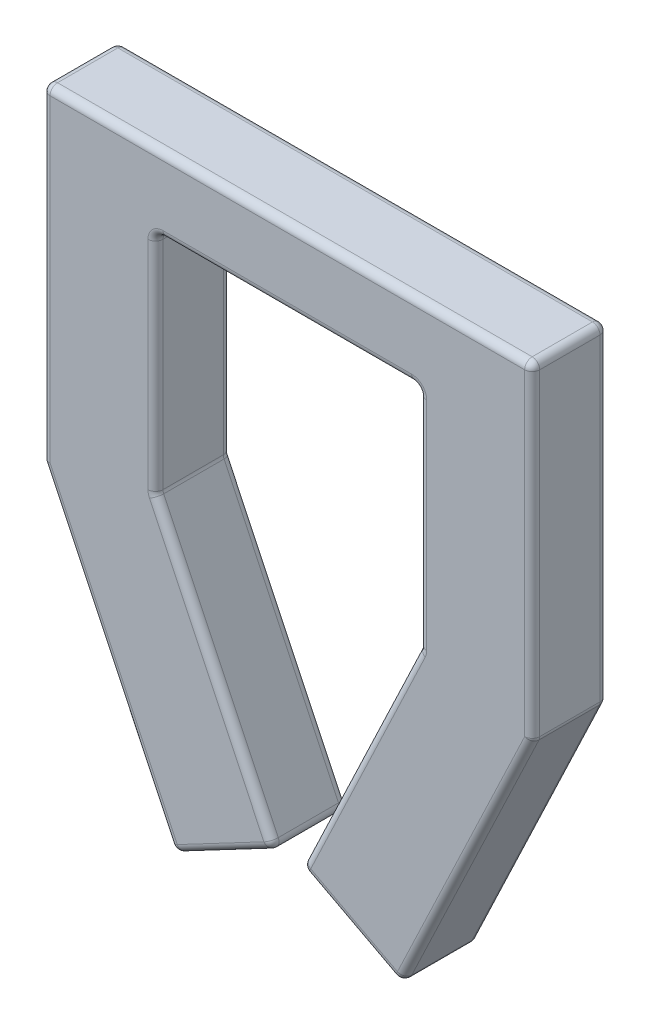
SolidWorks part; units mm, degrees
ref_plane "Front Plane" through (0, 0, 0) normal (0, 0, 1) x (1, 0, 0)
ref_plane "Top Plane" through (0, 0, 0) normal (0, 1, 0) x (1, 0, 0)
ref_plane "Right Plane" through (0, 0, 0) normal (1, 0, 0) x (0, 0, -1)
sketch "Sketch1" plane through (0, 0, 0) normal (0, 0, 1) x (1, 0, 0)
  line L0 (0, 0) -> (0, 80)
  line L1 (0, 80) -> (65, 80)
  line L2 (0, 0) -> (65, 0) construction
  line L3 (65, 0) -> (65, 80) construction
  line L4 (19.4871, 80) -> (19.4871, 70) construction
  line L5 (32.5, 70) -> (32.5, 0) construction
  line L6 (50, 40) -> (34.2919, 7.0063)
  line L7 (15, 40) -> (15, 70)
  line L8 (15, 70) -> (50, 70)
  line L9 (50, 70) -> (50, 40)
  line L10 (65, 40) -> (0, 40) construction
  line L11 (0, 40) -> (0, 80)
  line L12 (0, 40) -> (0, 85) construction
  line L13 (65, 80) -> (65, 36.6115)
  line L14 (65, 36.6115) -> (47.5695, 0)
  line L15 (0, 85) -> (65, 85) construction
  line L16 (65, 85) -> (65, 36.6115) construction
  line L17 (65, 36.6115) -> (47.8354, 0.5583) construction
  line L18 (34.2919, 7.0063) -> (47.5695, 0)
  line L19 (30.7081, 7.0063) -> (17.4305, 0)
  line L20 (0, 36.6115) -> (17.4305, 0)
  line L21 (15, 40) -> (30.7081, 7.0063)
extrude "Boss-Extrude1" add sketch "Sketch1" along normal blind 10 contours L21 L7 L8 L9 L6 L18 L14 L13 L1 L0 L20 L19
fillet "Fillet1" radius 1 35 edges at (24.0693, 3.5031, 10) (8.7152, 18.3058, 10) (0, 58.3058, 10) (32.5, 80, 10) (65, 58.3058, 10) (40.9307, 3.5031, 10) (42.146, 23.5031, 10) (50, 55, 10) (32.5, 70, 10) (15, 55, 10) (22.854, 23.5031, 10) (47.5695, 0, 5) (56.2848, 18.3058, 10) (65, 36.6115, 5) (56.2848, 18.3058, 0) (15, 40, 5) (15, 70, 5) (50, 70, 5) (50, 40, 5) (34.2919, 7.0063, 5) (65, 80, 5) (0, 80, 5) (17.4305, 0, 5) (30.7081, 7.0063, 5) (24.0693, 3.5031, 0) (8.7152, 18.3058, 0) (0, 58.3058, 0) (32.5, 80, 0) (65, 58.3058, 0) (40.9307, 3.5031, 0) (42.146, 23.5031, 0) (50, 55, 0) (32.5, 70, 0) (15, 55, 0) (22.854, 23.5031, 0)
